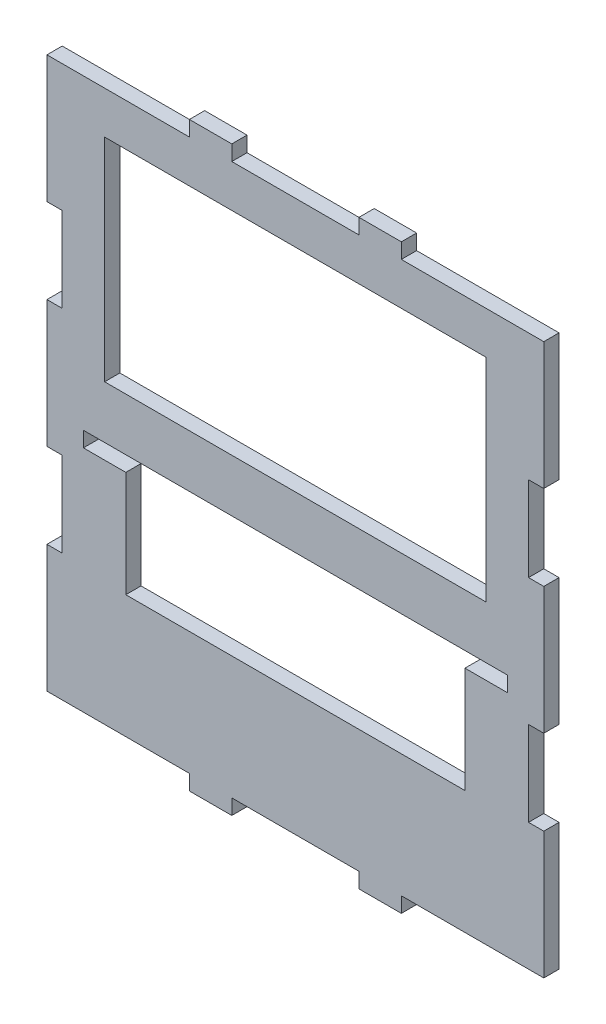
SolidWorks part; units mm, degrees
ref_plane "Front Plane" through (0, 0, 0) normal (0, 0, 1) x (1, 0, 0)
ref_plane "Top Plane" through (0, 0, 0) normal (0, 1, 0) x (1, 0, 0)
ref_plane "Right Plane" through (0, 0, 0) normal (1, 0, 0) x (0, 0, -1)
sketch "Sketch1" plane through (0, 0, 0) normal (0, 0, 1) x (1, 0, 0)
  line L1 (0, 0) -> (148.844, 0)
  line L2 (0, 0) -> (0, 174.244)
  line L3 (0, 174.244) -> (148.844, 174.244)
  line L4 (148.844, 0) -> (148.844, 174.244)
  dimension "D1" = 148.844
  dimension "D2" = 174.244
extrude "Boss-Extrude1" add sketch "Sketch1" along normal blind 4.572
sketch "Sketch2" plane through (0, 0, 4.572) normal (0, 0, 1) x (1, 0, 0)
  line L0 (0, 0) -> (148.844, 0) construction
  line L1 (0, 0) -> (42.672, 0)
  line L2 (0, 0) -> (0, 4.572)
  line L3 (0, 4.572) -> (42.672, 4.572)
  line L4 (42.672, 0) -> (42.672, 4.572)
  line L5 (55.372, 0) -> (93.472, 0)
  line L6 (55.372, 0) -> (55.372, 4.572)
  line L7 (55.372, 4.572) -> (93.472, 4.572)
  line L8 (93.472, 0) -> (93.472, 4.572)
  line L9 (148.844, 174.244) -> (0, 174.244) construction
  line L10 (148.844, 0) -> (106.172, 0)
  line L11 (148.844, 0) -> (148.844, 4.572)
  line L12 (148.844, 4.572) -> (106.172, 4.572)
  line L13 (106.172, 0) -> (106.172, 4.572)
  line L14 (0, 174.244) -> (42.672, 174.244)
  line L15 (0, 174.244) -> (0, 169.672)
  line L16 (0, 169.672) -> (42.672, 169.672)
  line L17 (42.672, 174.244) -> (42.672, 169.672)
  line L18 (148.844, 174.244) -> (106.172, 174.244)
  line L19 (148.844, 174.244) -> (148.844, 169.672)
  line L20 (148.844, 169.672) -> (106.172, 169.672)
  line L21 (106.172, 174.244) -> (106.172, 169.672)
  line L22 (55.372, 174.244) -> (93.472, 174.244)
  line L23 (55.372, 174.244) -> (55.372, 169.672)
  line L24 (55.372, 169.672) -> (93.472, 169.672)
  line L25 (93.472, 174.244) -> (93.472, 169.672)
  dimension "D1" = 4.572
  dimension "D2" = 4.572
  dimension "D3" = 4.572
  dimension "D4" = 42.672
  dimension "D5" = 42.672
  dimension "D6" = 38.1
  dimension "D7" = 12.7
  dimension "D8" = 4.572
  dimension "D9" = 4.572
  dimension "D10" = 4.572
  dimension "D11" = 42.672
  dimension "D12" = 42.672
  dimension "D13" = 38.1
  dimension "D14" = 12.7
extrude "Cut-Extrude1" cut sketch "Sketch2" against normal blind 45.72
sketch "Sketch3" plane through (0, 0, 4.572) normal (0, 0, 1) x (1, 0, 0)
  line L0 (148.844, 4.572) -> (148.844, 169.672) construction
  line L1 (148.844, 42.672) -> (144.272, 42.672)
  line L2 (148.844, 42.672) -> (148.844, 68.072)
  line L3 (148.844, 68.072) -> (144.272, 68.072)
  line L4 (144.272, 42.672) -> (144.272, 68.072)
  line L5 (0, 169.672) -> (0, 4.572) construction
  line L6 (0, 42.672) -> (4.572, 42.672)
  line L7 (0, 42.672) -> (0, 68.072)
  line L8 (0, 68.072) -> (4.572, 68.072)
  line L9 (4.572, 42.672) -> (4.572, 68.072)
  line L10 (42.672, 4.572) -> (0, 4.572) construction
  line L11 (148.844, 106.172) -> (144.272, 106.172)
  line L12 (148.844, 106.172) -> (148.844, 131.572)
  line L13 (148.844, 131.572) -> (144.272, 131.572)
  line L14 (144.272, 106.172) -> (144.272, 131.572)
  line L15 (0, 106.172) -> (4.572, 106.172)
  line L16 (0, 106.172) -> (0, 131.572)
  line L17 (0, 131.572) -> (4.572, 131.572)
  line L18 (4.572, 106.172) -> (4.572, 131.572)
  line L19 (0, 169.672) -> (42.672, 169.672) construction
  line L20 (148.844, 4.572) -> (106.172, 4.572) construction
  line L21 (106.172, 169.672) -> (148.844, 169.672) construction
  dimension "D1" = 4.572
  dimension "D2" = 4.572
  dimension "D3" = 4.572
  dimension "D4" = 4.572
  dimension "D5" = 25.4
  dimension "D6" = 25.4
  dimension "D7" = 25.4
  dimension "D8" = 38.1
  dimension "D9" = 25.4
  dimension "D10" = 38.1
  dimension "D11" = 38.1
  dimension "D12" = 38.1
extrude "Cut-Extrude2" cut sketch "Sketch3" against normal blind 45.72
sketch "Sketch4" plane through (0, 0, 0) normal (0, 0, -1) x (-1, 0, 0)
  line L0 (-148.844, 169.672) -> (-106.172, 169.672) construction
  line L1 (-17.272, 93.472) -> (-131.572, 93.472)
  line L2 (-17.272, 93.472) -> (-17.272, 156.972)
  line L3 (-17.272, 156.972) -> (-131.572, 156.972)
  line L4 (-131.572, 93.472) -> (-131.572, 156.972)
  line L5 (-4.572, 131.572) -> (-4.572, 106.172) construction
  line L7 (-4.572, 68.072) -> (-4.572, 42.672) construction
  line L8 (-23.622, 41.402) -> (-125.222, 41.402)
  line L9 (-23.622, 41.402) -> (-23.622, 73.152)
  line L10 (-23.622, 73.152) -> (-125.222, 73.152)
  line L11 (-125.222, 41.402) -> (-125.222, 73.152)
  dimension "D1" = 114.3
  dimension "D2" = 63.5
  dimension "D3" = 12.7
  dimension "D4" = 12.7
  dimension "D5" = 101.6
  dimension "D6" = 19.05
  dimension "D7" = 20.32
  dimension "D8" = 31.75
extrude "Cut-Extrude3" cut sketch "Sketch4" against normal blind 4.572
sketch "Sketch5" plane through (0, 0, 0) normal (0, 0, -1) x (-1, 0, 0)
  line L0 (-23.622, 73.152) -> (-125.222, 73.152) construction
  line L1 (-10.922, 73.152) -> (-137.922, 73.152)
  line L2 (-10.922, 73.152) -> (-10.922, 77.724)
  line L3 (-10.922, 77.724) -> (-137.922, 77.724)
  line L4 (-137.922, 73.152) -> (-137.922, 77.724)
  line L13 (-4.572, 68.072) -> (-4.572, 42.672) construction
  dimension "D1" = 4.572
  dimension "D2" = 6.35
  dimension "D3" = 127
extrude "Cut-Extrude4" cut sketch "Sketch5" against normal blind 4.572
equation "\"D1@Boss-Extrude1\"=0.18in"
equation "\"D1@Cut-Extrude1\"=1.8in"
